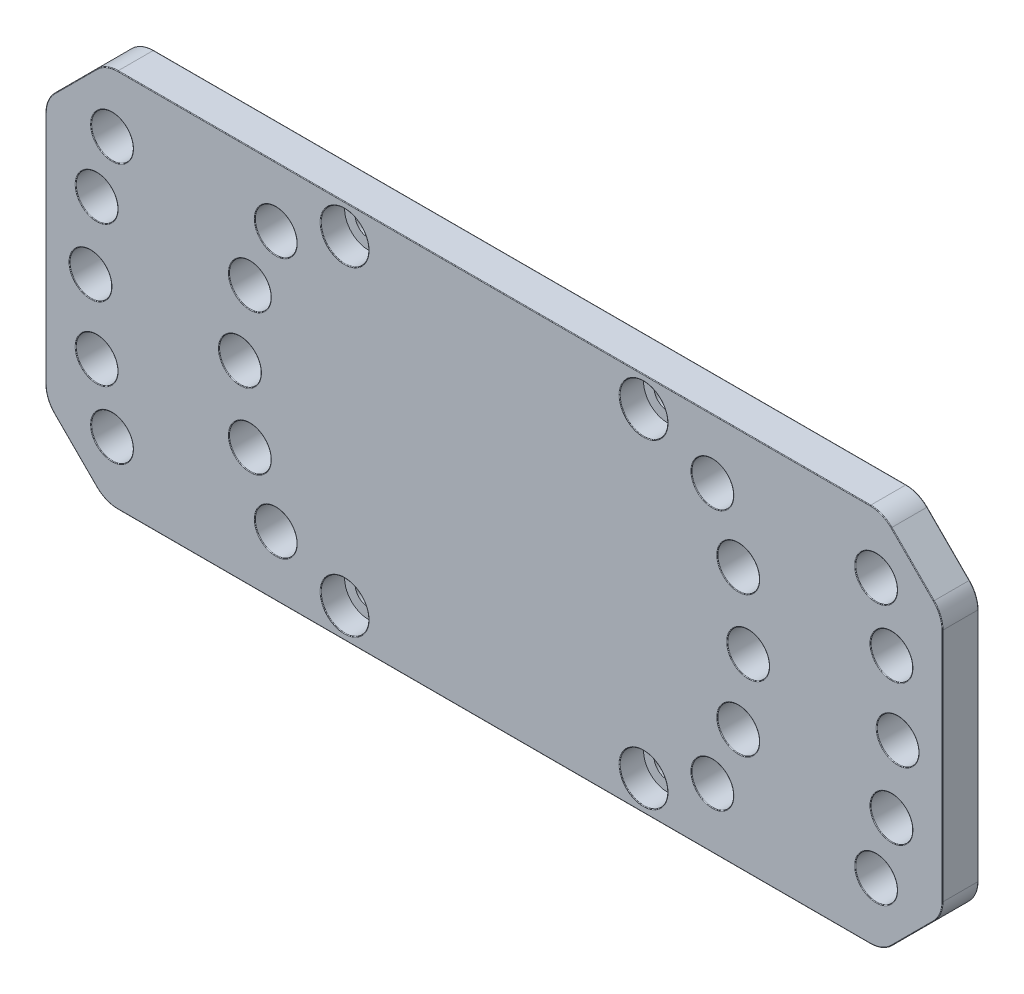
SolidWorks part; units mm, degrees
material "Сплав 2024"
ref_plane "Спереди" through (0, 0, 0) normal (0, 0, 1) x (1, 0, 0)
ref_plane "Сверху" through (0, 0, 0) normal (0, 1, 0) x (1, 0, 0)
ref_plane "Справа" through (0, 0, 0) normal (1, 0, 0) x (0, 0, -1)
sketch "Эскиз5" plane through (0, 0, 0) normal (0, 0, 1) x (1, 0, 0)
  line L0 (-75, 21.75) -> (-65, 31.75)
  line L1 (-65, 31.75) -> (65, 31.75)
  line L2 (-75, 21.75) -> (-75, -21.75)
  line L3 (-65, -31.75) -> (65, -31.75)
  line L4 (75, 21.75) -> (75, -21.75)
  line L5 (-75, 31.75) -> (75, -31.75) construction
  line L6 (-75, -31.75) -> (75, 31.75) construction
  line L7 (-75, -21.75) -> (-65, -31.75)
  line L8 (65, -31.75) -> (75, -21.75)
  line L9 (65, 31.75) -> (75, 21.75)
  point P0 (0, 0)
  dimension "D1" = 150
  dimension "D2" = 63.5
extrude "Бобышка-Вытянуть2" add sketch "Эскиз5" along normal blind 6
sketch "Эскиз6" plane through (0, 0, 6) normal (0, 0, 1) x (1, 0, 0)
  line L0 (-25, 31.75) -> (-25, -31.75) construction
  line L1 (65, 31.75) -> (-65, 31.75) construction
  line L2 (-65, -31.75) -> (65, -31.75) construction
  line L3 (25, 31.75) -> (25, -31.75) construction
  line L4 (-75, 21.75) -> (-75, -21.75) construction
  line L5 (75, -21.75) -> (75, 21.75) construction
  line L6 (-75, 26.75) -> (75, 26.75) construction
  line L7 (75, -26.75) -> (-75, -26.75) construction
  dimension "D1" = 50
  dimension "D2" = 50
  dimension "D3" = 5
  dimension "D4" = 5
hole_wizard "Цековка для винта с внутренним шестигранником M41" positions "Эскиз8" profile "Эскиз7" counterbore size "M4" standard "Ansi Metric" end condition through all
sketch "Эскиз8" plane through (0, 0, 6) normal (0, 0, 1) x (1, 0, 0)
  line L0 (-25, 31.75) -> (-25, -31.75) construction
  line L1 (-75, 26.75) -> (75, 26.75) construction
  line L2 (75, -26.75) -> (-75, -26.75) construction
  line L3 (25, 31.75) -> (25, -31.75) construction
  point P0 (-25, 26.75)
  point P6 (-25, -26.75)
  point P10 (25, -26.75)
  point P14 (25, 26.75)
sketch "Эскиз7" plane through (-25, 26.75, 6) normal (1, 0, 0) x (0, -1, 0)
  line L0 (0, 0) -> (0, 6)
  line L1 (0, 6) -> (2.25, 6)
  line L3 (2.25, 6) -> (2.25, 4)
  line L4 (2.25, 4) -> (4, 4)
  line L5 (4, 4) -> (4, 0)
  line L7 (4, 0) -> (0, 0)
  line L11 (0, -6.35) -> (0, 107.95) construction
  dimension "Диаметр сквозного отверстия" = 4.5
  dimension "Глубина сквозного отверстия" = 6
  dimension "Диаметр цековки" = 8
  dimension "Глубина цековки" = 4
sketch "Эскиз13" plane through (0, 0, 6) normal (0, 0, 1) x (1, 0, 0)
  line L11 (-75, 0) -> (75, 0) construction
  line L12 (-75, 21.75) -> (-75, -21.75) construction
  line L13 (75, -21.75) -> (75, 21.75) construction
  line L14 (-75, 11.75) -> (75, 11.75) construction
  line L15 (-75, 21.75) -> (75, 21.75) construction
  line L16 (65, 31.75) -> (-65, 31.75) construction
  line L17 (-75, -11.75) -> (75, -11.75) construction
  line L18 (-75, -21.75) -> (75, -21.75) construction
  line L19 (0, 31.75) -> (0, -31.75) construction
  line L20 (-65, -31.75) -> (65, -31.75) construction
  circle A0 centre (-67.5, 0) radius 3.5
  circle A1 centre (0, 0) radius 67.5 construction
  circle A2 centre (0, 0) radius 55 construction
  circle A3 centre (0, 0) radius 42.5 construction
  circle A4 centre (-66.4694, 11.75) radius 3.5
  circle A5 centre (-63.8998, 21.75) radius 3.5
  circle A6 centre (-66.4694, -11.75) radius 3.5
  circle A7 centre (-63.8998, -21.75) radius 3.5
  circle A8 centre (63.8998, -21.75) radius 3.5
  circle A9 centre (66.4694, -11.75) radius 3.5
  circle A10 centre (67.5, 0) radius 3.5
  circle A11 centre (66.4694, 11.75) radius 3.5
  circle A12 centre (63.8998, 21.75) radius 3.5
  circle A13 centre (-36.5128, 21.75) radius 3.5
  circle A14 centre (-40.8435, 11.75) radius 3.5
  circle A15 centre (-42.5, 0) radius 3.5
  circle A16 centre (-40.8435, -11.75) radius 3.5
  circle A17 centre (-36.5128, -21.75) radius 3.5
  circle A18 centre (36.5128, -21.75) radius 3.5
  circle A19 centre (40.8435, -11.75) radius 3.5
  circle A20 centre (42.5, 0) radius 3.5
  circle A21 centre (40.8435, 11.75) radius 3.5
  circle A22 centre (36.5128, 21.75) radius 3.5
  dimension "D1" = 135
  dimension "D2" = 10
  dimension "D3" = 20
  dimension "D4" = 110
  dimension "D5" = 85
  dimension "D6" = 7
  dimension "D7" = 7
  dimension "D8" = 7
  dimension "D9" = 7
  dimension "D10" = 7
  dimension "D11" = 7
  dimension "D12" = 7
  dimension "D13" = 7
  dimension "D14" = 7
  dimension "D15" = 7
extrude "Вырез-Вытянуть1" cut sketch "Эскиз13" against normal through all
fillet "Скругление1" radius 5 8 edges at (65, 31.75, 3) (75, 21.75, 3) (75, -21.75, 3) (65, -31.75, 3) (-65, -31.75, 3) (-75, -21.75, 3) (-75, 21.75, 3) (-65, 31.75, 3)
fillet "Скругление2" radius 0.1 80 edges at (-64.8423, 31.3694, 0) (-70, 26.75, 0) (-74.6194, 21.5923, 0) (-75, 0, 0) (-74.6194, -21.5923, 0) (-70, -26.75, 0) (-64.8423, -31.3694, 0) (0, -31.75, 0) (64.8423, -31.3694, 0) (70, -26.75, 0) (74.6194, -21.5923, 0) (75, 0, 0) (74.6194, 21.5923, 0) (70, 26.75, 0) (64.8423, 31.3694, 0) (0, 31.75, 0) (27.25, 26.75, 0) (27.25, -26.75, 0) (-22.75, -26.75, 0) (-22.75, 26.75, 0) (74.6194, 21.5923, 6) (75, 0, 6) (74.6194, -21.5923, 6) (70, -26.75, 6) (64.8423, -31.3694, 6) (0, -31.75, 6) (-64.8423, -31.3694, 6) (-70, -26.75, 6) (-74.6194, -21.5923, 6) (-75, 0, 6) (-74.6194, 21.5923, 6) (-70, 26.75, 6) (-64.8423, 31.3694, 6) (0, 31.75, 6) (64.8423, 31.3694, 6) (70, 26.75, 6) (29, 26.75, 6) (29, -26.75, 6) (-21, -26.75, 6) (-21, 26.75, 6) (-64, 0, 0) (-64, 0, 6) (-62.9694, 11.75, 0) (-60.3998, 21.75, 0) (-62.9694, -11.75, 0) (-60.3998, -21.75, 0) (60.3998, -21.75, 0) (62.9694, -11.75, 0) (64, 0, 0) (62.9694, 11.75, 0) (60.3998, 21.75, 0) (-33.0128, 21.75, 0) (-37.3435, 11.75, 0) (-39, 0, 0) (-37.3435, -11.75, 0) (-33.0128, -21.75, 0) (33.0128, -21.75, 0) (37.3435, -11.75, 0) (39, 0, 0) (37.3435, 11.75, 0) (33.0128, 21.75, 0) (-62.9694, 11.75, 6) (-60.3998, 21.75, 6) (-62.9694, -11.75, 6) (-60.3998, -21.75, 6) (60.3998, -21.75, 6) (62.9694, -11.75, 6) (64, 0, 6) (62.9694, 11.75, 6) (60.3998, 21.75, 6) (-33.0128, 21.75, 6) (-37.3435, 11.75, 6) (-39, 0, 6) (-37.3435, -11.75, 6) (-33.0128, -21.75, 6) (33.0128, -21.75, 6) (37.3435, -11.75, 6) (39, 0, 6) (37.3435, 11.75, 6) (33.0128, 21.75, 6)
